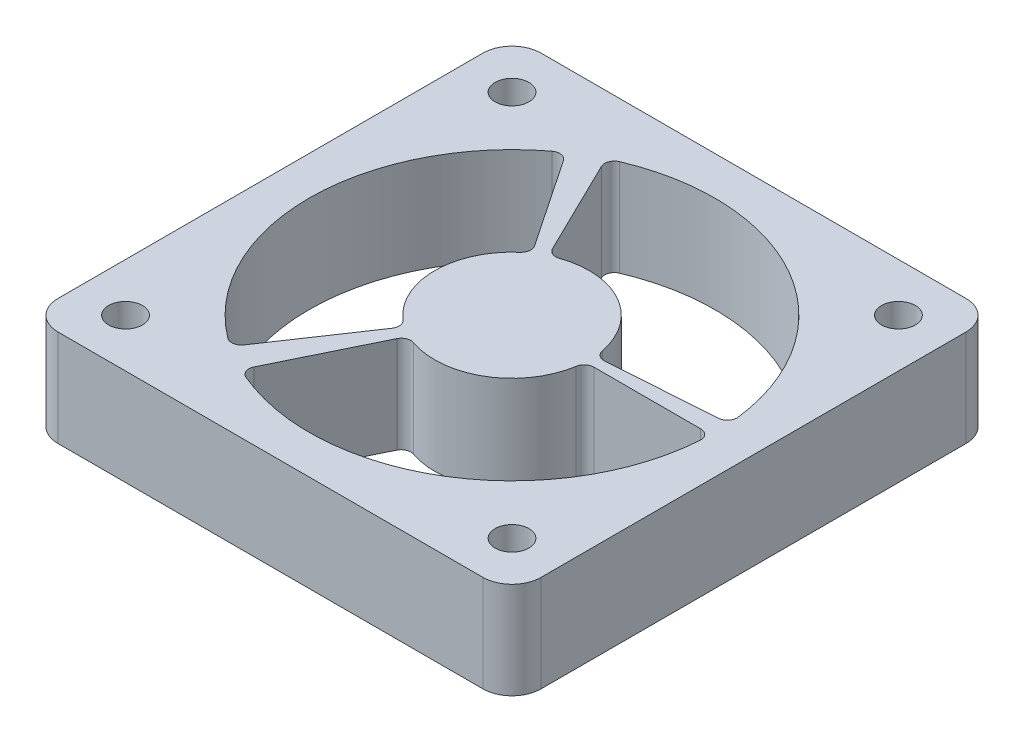
SolidWorks part; units mm, degrees
ref_plane "Płaszczyzna przednia" through (0, 0, 0) normal (0, 0, 1) x (1, 0, 0)
ref_plane "Płaszczyzna górna" through (0, 0, 0) normal (0, 1, 0) x (1, 0, 0)
ref_plane "Płaszczyzna prawa" through (0, 0, 0) normal (1, 0, 0) x (0, 0, -1)
sketch "Szkic1" plane through (0, 0, 0) normal (0, 1, 0) x (1, 0, 0)
  line L1 (22, -25) -> (-22, -25)
  line L2 (25, -22) -> (25, 22)
  line L3 (22, 25) -> (-22, 25)
  line L4 (-25, -22) -> (-25, 22)
  line L5 (25, -25) -> (-25, 25) construction
  line L6 (25, 25) -> (-25, -25) construction
  arc A0 (-22, -25) -> (-25, -22) centre (-22, -22) cw
  arc A1 (22, -25) -> (25, -22) centre (22, -22) ccw
  arc A2 (25, 22) -> (22, 25) centre (22, 22) ccw
  arc A3 (-25, 22) -> (-22, 25) centre (-22, 22) cw
  point P0 (0, 0)
  dimension "D3" = 3
  dimension "D1" = 50
  dimension "D2" = 50
extrude "Dodanie-wyciągnięcie1" add sketch "Szkic1" along normal blind 10
sketch "Szkic2" plane through (0, 10, 0) normal (0, 1, 0) x (1, 0, 0)
  line L0 (19.9498, -0.4161) -> (8.8879, -0.4161)
  line L1 (-25, 22) -> (-25, -22) construction
  line L2 (22, 25) -> (-22, 25) construction
  line L3 (19.9188, 1.4498) -> (8.9101, 0.6868)
  line L10 (-8.7129, -17.971) -> (-3.8667, -8.0573)
  line L11 (-11.2069, -16.5311) -> (-5.0444, -7.3773)
  line L12 (-11.2069, 16.5311) -> (-5.0444, 7.3773)
  line L13 (-8.7129, 17.971) -> (-3.8667, 8.0573)
  circle A0 centre (-20, 20) radius 1.75
  circle A1 centre (20, 20) radius 1.75
  circle A2 centre (20, -20) radius 1.75
  circle A3 centre (-20, -20) radius 1.75
  arc A5 (-8.2052, -19.3307) -> (20.9473, -1.4869) centre (0, 0) ccw
  arc A6 (20.8422, 2.5698) -> (-8.2052, 19.3307) centre (0, 0) ccw
  arc A7 (-5.2213, 6.0612) -> (-5.2213, -6.0612) centre (0, 0) ccw
  arc A8 (-12.6382, 16.7713) -> (-12.6382, -16.7713) centre (0, 0) ccw
  arc A9 (-2.6385, -7.5524) -> (7.9004, -1.2587) centre (0, 0) ccw
  arc A10 (7.8586, 1.4973) -> (-2.6385, 7.5524) centre (0, 0) ccw
  arc A11 (-11.2069, 16.5311) -> (-12.6382, 16.7713) centre (-12.0364, 15.9726) ccw
  arc A12 (-12.6382, -16.7713) -> (-11.2069, -16.5311) centre (-12.0364, -15.9726) ccw
  arc A13 (-5.0444, -7.3773) -> (-5.2213, -6.0612) centre (-5.874, -6.8188) ccw
  arc A14 (-5.2213, 6.0612) -> (-5.0444, 7.3773) centre (-5.874, 6.8188) ccw
  arc A15 (-8.7129, -17.971) -> (-8.2052, -19.3307) centre (-7.8145, -18.4102) ccw
  arc A16 (-8.7129, 17.971) -> (-8.2052, 19.3307) centre (-7.8145, 18.4102) cw
  arc A17 (19.9188, 1.4498) -> (20.8422, 2.5698) centre (19.8497, 2.4475) ccw
  arc A18 (7.8586, 1.4973) -> (8.9101, 0.6868) centre (8.841, 1.6844) ccw
  arc A19 (-3.8667, 8.0573) -> (-2.6385, 7.5524) centre (-2.9683, 8.4964) ccw
  arc A20 (-3.8667, -8.0573) -> (-2.6385, -7.5524) centre (-2.9683, -8.4964) cw
  arc A21 (20.9473, -1.4869) -> (19.9498, -0.4161) centre (19.9498, -1.4161) ccw
  arc A22 (8.8879, -0.4161) -> (7.9004, -1.2587) centre (8.8879, -1.4161) ccw
  dimension "D1" = 5
  dimension "D3" = 1
  dimension "D4" = 1
  dimension "D5" = 3.5
  dimension "D8" = 21
  dimension "D9" = 8
  dimension "D2" = 5
  dimension "D6" = 40
  dimension "D7" = 40
extrude "Wytnij-wyciągnięcie1" cut sketch "Szkic2" against normal blind 10
